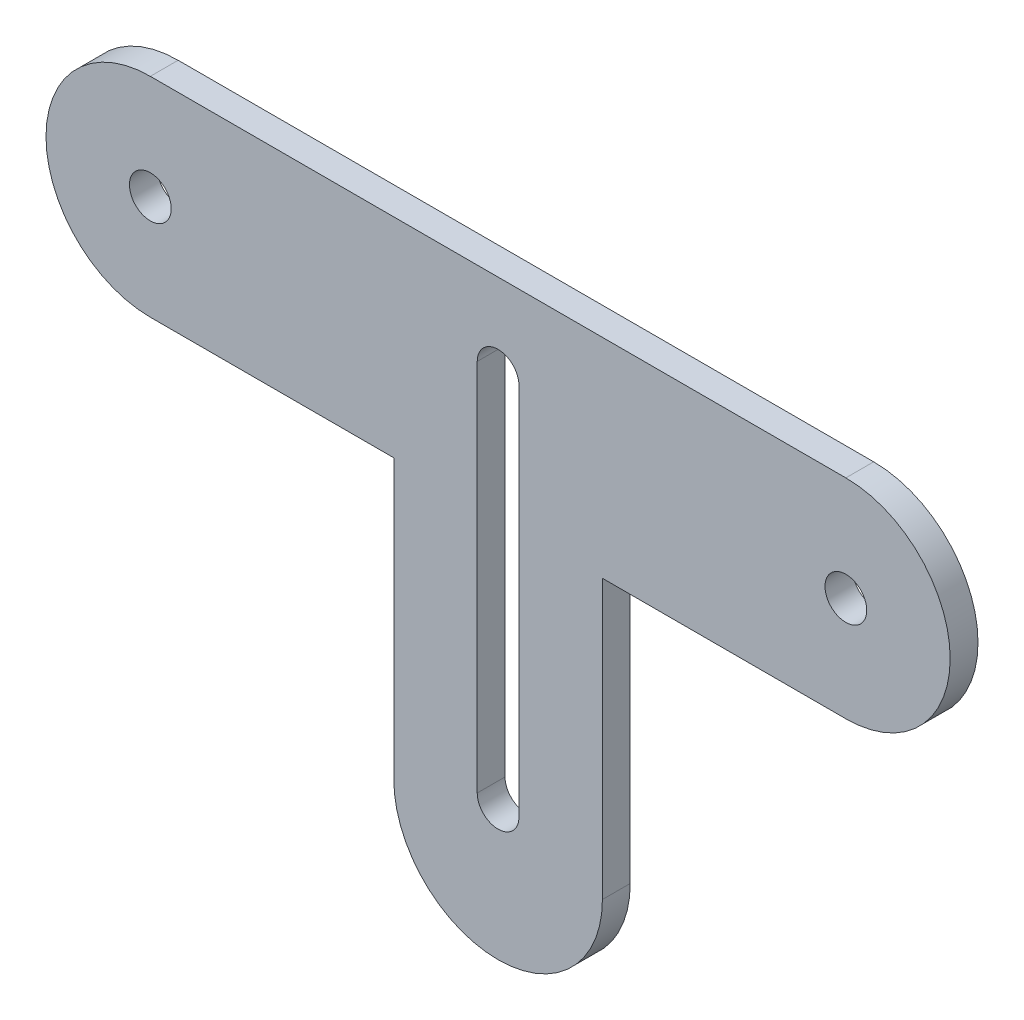
SolidWorks part; units mm, degrees
ref_plane "前视基准面" through (0, 0, 0) normal (0, 0, 1) x (1, 0, 0)
ref_plane "上视基准面" through (0, 0, 0) normal (0, 1, 0) x (1, 0, 0)
ref_plane "右视基准面" through (0, 0, 0) normal (1, 0, 0) x (0, 0, -1)
sketch "草图1" plane through (0, 0, 0) normal (0, 0, 1) x (1, 0, 0)
  line L0 (-35.2443, 2.233) -> (14.7557, 2.233)
  line L1 (-35.2443, -12.767) -> (-17.7443, -12.767)
  line L2 (14.7557, -12.767) -> (-2.7443, -12.767)
  line L3 (-2.7443, -12.767) -> (-2.7443, -32.767)
  line L4 (-17.7443, -12.767) -> (-17.7443, -32.767)
  arc A0 (-35.2443, 2.233) -> (-35.2443, -12.767) centre (-35.2443, -5.267) ccw
  arc A1 (14.7557, 2.233) -> (14.7557, -12.767) centre (14.7557, -5.267) cw
  arc A2 (-2.7443, -32.767) -> (-17.7443, -32.767) centre (-10.2443, -32.767) cw
  point P11 (-10.1774, -23.9966)
  point P12 (0, 0)
  dimension "D1" = 50
  dimension "D2" = 7.5
  dimension "D3" = 7.5
  dimension "D7" = 7.5
  dimension "D9" = 15
  dimension "D4" = 20
  dimension "D5" = 17.5
  dimension "D6" = 17.5
  dimension "D8" = 20
extrude "凸台-拉伸1" add sketch "草图1" along normal blind 2
sketch "草图2" plane through (0, 0, 2) normal (0, 0, 1) x (1, 0, 0)
  line L0 (-11.7443, -3.767) -> (-11.7443, -30.6354)
  line L1 (-8.7443, -3.767) -> (-8.7443, -30.6354)
  line L3 (14.7557, 2.233) -> (-35.2443, 2.233) construction
  line L7 (-2.7443, -32.767) -> (-2.7443, -12.767) construction
  line L8 (-17.7443, -12.767) -> (-17.7443, -32.767) construction
  arc A0 (-11.7443, -3.767) -> (-8.7443, -3.767) centre (-10.2443, -3.767) cw
  arc A1 (-8.7443, -30.6354) -> (-11.7443, -30.6354) centre (-10.2443, -30.6354) cw
  dimension "D1" = 1.5
  dimension "D2" = 6
  dimension "D5" = 1.5
  dimension "D3" = 6
  dimension "D4" = 6
extrude "切除-拉伸2" cut sketch "草图2" against normal through all
sketch "草图3" plane through (0, 0, 0) normal (0, 0, -1) x (-1, 0, 0)
  line L1 (-14.7557, 2.233) -> (35.2443, 2.233) construction
  line L5 (8.7443, -30.6354) -> (8.7443, -3.767) construction
  line L6 (11.7443, -3.767) -> (11.7443, -30.6354) construction
  circle A0 centre (-14.7557, -5.267) radius 1.5
  circle A1 centre (35.2443, -5.267) radius 1.5
  dimension "D1" = 3
  dimension "D2" = 7.5
  dimension "D3" = 23.5
  dimension "D4" = 23.5
extrude "切除-拉伸1" cut sketch "草图3" against normal through all
